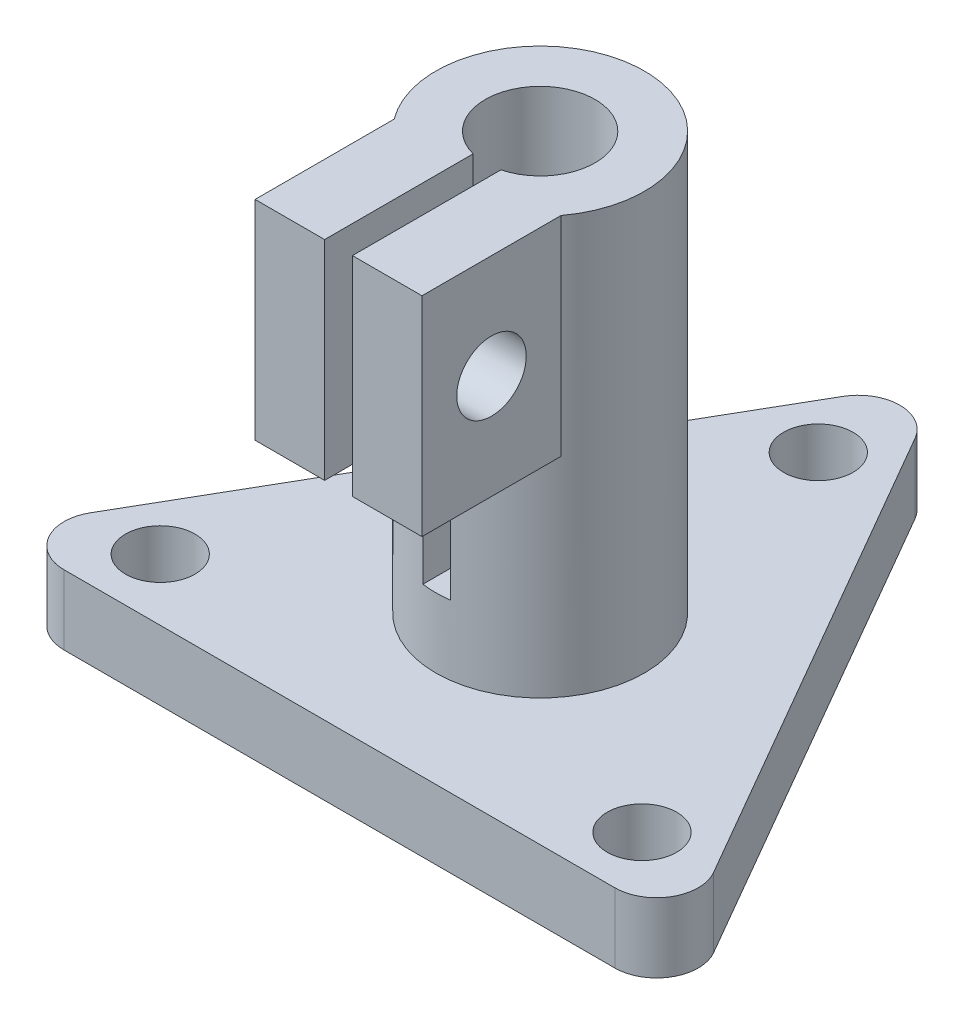
SolidWorks part; units mm, degrees
ref_plane "Plan de face" through (0, 0, 0) normal (0, 0, 1) x (1, 0, 0)
ref_plane "Plan de dessus" through (0, 0, 0) normal (0, 1, 0) x (1, 0, 0)
ref_plane "Plan de droite" through (0, 0, 0) normal (1, 0, 0) x (0, 0, -1)
sketch "Esquisse5" plane through (0, 0, 0) normal (0, 1, 0) x (1, 0, 0)
  line L0 (-25, -14.4338) -> (25, -14.4338)
  line L1 (25, -14.4338) -> (0, 28.8675)
  line L2 (0, 28.8675) -> (-25, -14.4338)
  line L3 (12.5, 7.2169) -> (-25, -14.4338) construction
  line L4 (-12.5, 7.2169) -> (25, -14.4338) construction
  circle A0 centre (0, 20) radius 2.5
  circle A1 centre (-17.3205, -10) radius 2.5
  circle A2 centre (17.3205, -10) radius 2.5
  dimension "D1" = 5
  dimension "D2" = 20
  dimension "D3" = 20
  dimension "D4" = 20
  dimension "D5" = 50
extrude "Boss.-Extru.2" add sketch "Esquisse5" along normal blind 5
sketch "Esquisse6" plane through (0, 5, 0) normal (0, 1, 0) x (1, 0, 0)
  circle A0 centre (0, 0) radius 7.5
  dimension "D1" = 15
extrude "Boss.-Extru.3" add sketch "Esquisse6" along normal blind 30
sketch "Esquisse13" plane through (0, 35, 0) normal (0, 1, 0) x (1, 0, 0)
  line L1 (-6, -4.5) -> (-6, -14.5)
  line L2 (6, -4.5) -> (6, -14.5)
  line L3 (-6, -14.5) -> (6, -14.5)
  circle A0 centre (0, 0) radius 7.5 construction
  circle A1 centre (0, 0) radius 7.5 construction
  arc A2 (-6, -4.5) -> (6, -4.5) centre (0, 0) ccw
  point P8 (0, -14.5)
  dimension "D1" = 12
  dimension "D2" = 10
extrude "Boss.-Extru.6" add sketch "Esquisse13" against normal blind 15
sketch "Esquisse14" plane through (0, 35, 0) normal (0, 1, 0) x (1, 0, 0)
  circle A0 centre (0, 0) radius 3.95
  dimension "D1" = 7.9
extrude "Enlèv. mat.-Extru.4" cut sketch "Esquisse14" against normal through all
sketch "Esquisse15" plane through (0, 35, 0) normal (0, 1, 0) x (1, 0, 0)
  line L1 (-1, -3.8213) -> (-1, -14.5)
  line L2 (1, -3.8213) -> (1, -14.5)
  line L3 (-1, -14.5) -> (1, -14.5)
  line L4 (-6, -14.5) -> (6, -14.5) construction
  circle A0 centre (0, 0) radius 3.95 construction
  arc A1 (-1, -3.8213) -> (1, -3.8213) centre (0, 0) ccw
  dimension "D1" = 2
extrude "Enlèv. mat.-Extru.5" cut sketch "Esquisse15" against normal blind 25
fillet "Congé2" radius 3 3 edges at (0, 2.5, -28.8675) (-25, 2.5, 14.4338) (25, 2.5, 14.4338)
sketch "Esquisse17" plane through (6, 0, 0) normal (1, 0, 0) x (0, 0, -1)
  line L0 (-14.5, 35) -> (-4.5, 35) construction
  line L1 (-14.5, 20) -> (-14.5, 35) construction
  circle A0 centre (-9.5, 27.5) radius 2.5
  dimension "D1" = 5
  dimension "D2" = 7.5
  dimension "D3" = 5
extrude "Enlèv. mat.-Extru.6" cut sketch "Esquisse17" against normal through all
sketch "Esquisse18" plane through (-6, 0, 0) normal (-1, 0, 0) x (0, 0, 1)
  line L0 (4.5, 35) -> (14.5, 35) construction
  line L1 (11.7863, 31.46) -> (7.2137, 31.46)
  line L2 (7.2137, 31.46) -> (4.9274, 27.5)
  line L3 (4.9274, 27.5) -> (7.2137, 23.54)
  line L4 (7.2137, 23.54) -> (11.7863, 23.54)
  line L5 (11.7863, 23.54) -> (14.0726, 27.5)
  line L6 (14.0726, 27.5) -> (11.7863, 31.46)
  circle A0 centre (9.5, 27.5) radius 3.96 construction
  dimension "D1" = 7.92
extrude "Enlèv. mat.-Extru.7" cut sketch "Esquisse18" against normal blind 4.5
